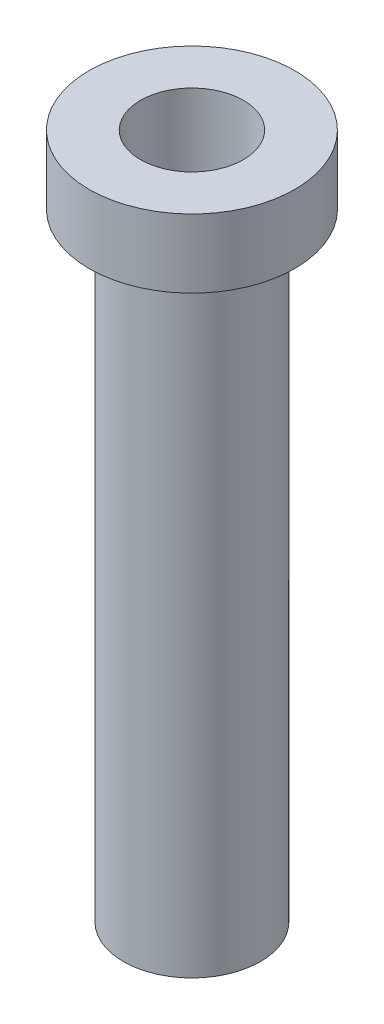
SolidWorks part; units mm, degrees
ref_plane "Front Plane" through (0, 0, 0) normal (0, 0, 1) x (1, 0, 0)
ref_plane "Top Plane" through (0, 0, 0) normal (0, 1, 0) x (1, 0, 0)
ref_plane "Right Plane" through (0, 0, 0) normal (1, 0, 0) x (0, 0, -1)
sketch "Sketch1" plane through (0, 0, 0) normal (0, 1, 0) x (1, 0, 0)
  circle A0 centre (0, 0) radius 7.5
  circle A1 centre (0, 0) radius 10
  dimension "D1" = 15
  dimension "D2" = 20
extrude "Boss-Extrude1" add sketch "Sketch1" along normal blind 100
sketch "Sketch2" plane through (0, 100, 0) normal (0, 1, 0) x (1, 0, 0)
  circle A0 centre (0, 0) radius 10 construction
  circle A1 centre (0, 0) radius 10
  circle A2 centre (0, 0) radius 15
  dimension "D1" = 30
extrude "Boss-Extrude2" add sketch "Sketch2" against normal blind 10
